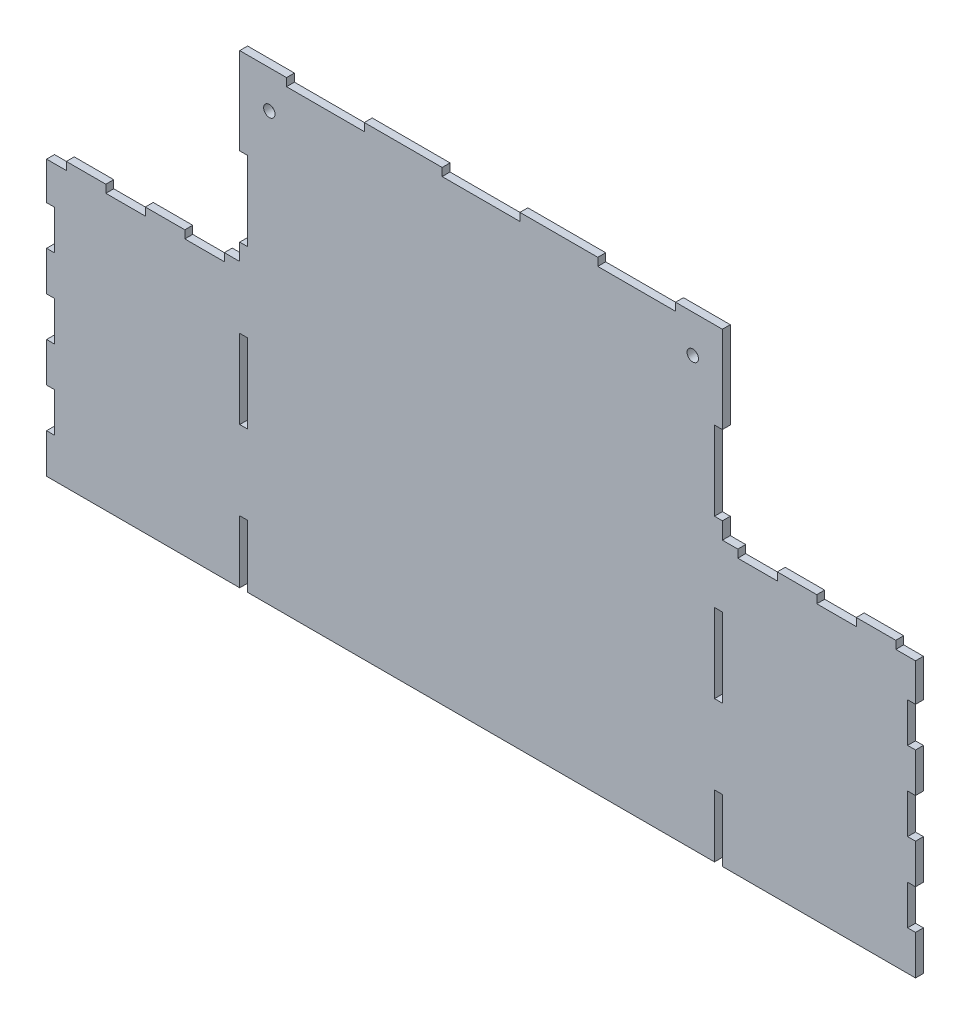
SolidWorks part; units mm, degrees
ref_plane "Front Plane" through (0, 0, 0) normal (0, 0, 1) x (1, 0, 0)
ref_plane "Top Plane" through (0, 0, 0) normal (0, 1, 0) x (1, 0, 0)
ref_plane "Right Plane" through (0, 0, 0) normal (1, 0, 0) x (0, 0, -1)
sketch "Sketch1" plane through (0, 0, 0) normal (0, 0, 1) x (1, 0, 0)
  line L1 (-77.597, 74.803) -> (77.597, 74.803)
  line L2 (-77.597, 74.803) -> (-77.597, -74.803)
  line L3 (-77.597, -74.803) -> (77.597, -74.803)
  line L4 (77.597, 74.803) -> (77.597, -74.803)
  line L5 (-77.597, 74.803) -> (77.597, -74.803) construction
  line L6 (-77.597, -74.803) -> (77.597, 74.803) construction
  point P0 (0, 0)
  dimension "D1" = 155.194
  dimension "D2" = 149.606
extrude "Boss-Extrude1" add sketch "Sketch1" along normal blind 2.54
sketch "Sketch2" plane through (0, 0, 2.54) normal (0, 0, 1) x (1, 0, 0)
  line L1 (-77.597, -74.803) -> (-139.7, -74.803)
  line L2 (-77.597, -74.803) -> (-77.597, 16.0655)
  line L3 (-77.597, 16.0655) -> (-139.7, 16.0655)
  line L4 (-139.7, -74.803) -> (-139.7, 16.0655)
  dimension "D1" = 62.103
  dimension "D2" = 90.8685
extrude "Boss-Extrude2" add sketch "Sketch2" against normal blind 2.54
sketch "Sketch3" plane through (0, 0, 2.54) normal (0, 0, 1) x (1, 0, 0)
  line L0 (-77.597, 74.803) -> (-77.597, 16.0655) construction
  line L1 (-77.597, 46.863) -> (-75.057, 46.863)
  line L2 (-77.597, 46.863) -> (-77.597, 21.463)
  line L3 (-77.597, 21.463) -> (-75.057, 21.463)
  line L4 (-75.057, 46.863) -> (-75.057, 21.463)
  line L5 (77.597, 74.803) -> (-77.597, 74.803) construction
  dimension "D1" = 27.94
  dimension "D2" = 25.4
  dimension "D3" = 2.54
extrude "Cut-Extrude1" cut sketch "Sketch3" against normal through all
pattern_linear "LPattern1" count 3 spacing 50.8 along (0, -1, 0) of "Cut-Extrude1"
mirror "Mirror1" about plane through (0, 0, 0) normal (1, 0, 0) of "LPattern1", "Boss-Extrude2", "Cut-Extrude1"
sketch "Sketch4" plane through (0, 0, 2.54) normal (0, 0, 1) x (1, 0, 0)
  line L0 (-77.597, 16.0655) -> (-139.7, 16.0655) construction
  line L1 (-146.05, 16.0655) -> (-133.35, 16.0655)
  line L2 (-146.05, 16.0655) -> (-146.05, 13.5255)
  line L3 (-146.05, 13.5255) -> (-133.35, 13.5255)
  line L4 (-133.35, 16.0655) -> (-133.35, 13.5255)
  line L5 (-139.7, 16.0655) -> (-139.7, -74.803) construction
  dimension "D1" = 12.7
  dimension "D2" = 2.54
  dimension "D3" = 6.35
extrude "Cut-Extrude2" cut sketch "Sketch4" against normal through all
pattern_linear "LPattern2" count 3 spacing 25.4 along (1, 0, 0) of "Cut-Extrude2"
mirror "Mirror2" about plane through (0, 0, 0) normal (1, 0, 0) of "LPattern2", "Cut-Extrude2"
sketch "Sketch5" plane through (0, 0, 2.54) normal (0, 0, 1) x (1, 0, 0)
  line L0 (-139.7, -74.803) -> (-77.597, -74.803) construction
  line L1 (-139.7, -62.103) -> (-137.16, -62.103)
  line L2 (-139.7, -62.103) -> (-139.7, -49.403)
  line L3 (-139.7, -49.403) -> (-137.16, -49.403)
  line L4 (-137.16, -62.103) -> (-137.16, -49.403)
  line L5 (-139.7, 13.5255) -> (-139.7, -74.803) construction
  point P4 (-138.43, -62.103)
  dimension "D1" = 2.54
  dimension "D2" = 12.7
  dimension "D3" = 12.7
extrude "Cut-Extrude3" cut sketch "Sketch5" against normal blind 2.54
pattern_linear "LPattern3" count 4 spacing 25.4 along (0, 1, 0) of "Cut-Extrude3"
mirror "Mirror3" about plane through (0, 0, 0) normal (1, 0, 0) of "LPattern3", "Cut-Extrude3"
sketch "Sketch6" plane through (0, 0, 2.54) normal (0, 0, 1) x (1, 0, 0)
  line L0 (77.597, 74.803) -> (-77.597, 74.803) construction
  line L1 (-62.5475, 74.803) -> (-37.5285, 74.803)
  line L2 (-62.5475, 74.803) -> (-62.5475, 72.263)
  line L3 (-62.5475, 72.263) -> (-37.5285, 72.263)
  line L4 (-37.5285, 74.803) -> (-37.5285, 72.263)
  line L5 (-77.597, 74.803) -> (-77.597, 46.863) construction
  dimension "D1" = 15.0495
  dimension "D2" = 25.019
  dimension "D3" = 2.54
extrude "Cut-Extrude4" cut sketch "Sketch6" against normal blind 2.54
pattern_linear "LPattern4" count 3 spacing 50.038 along (1, 0, 0) of "Cut-Extrude4"
hole_wizard "#6 Clearance Hole1" positions "Sketch8" profile "Sketch9" hole size "#6" standard "ANSI Inch"
sketch "Sketch8" plane through (0, 0, 2.54) normal (0, 0, 1) x (1, 0, 0)
  line L0 (-77.597, 74.803) -> (-77.597, 46.863) construction
  line L2 (77.597, 46.863) -> (77.597, 74.803) construction
  line L3 (-62.5475, 72.263) -> (-37.5285, 72.263) construction
  point P0 (-68.072, 62.738)
  point P2 (68.072, 62.738)
  dimension "D1" = 9.525
  dimension "D2" = 9.525
  dimension "D3" = 9.525
sketch "Sketch9" plane through (-68.072, 62.738, 2.54) normal (1, 0, 0) x (0, -1, 0)
  line L0 (0, 0) -> (0, 10.4969)
  line L1 (0, 10.4969) -> (1.8288, 9.398)
  line L2 (1.8288, 9.398) -> (1.8288, 0)
  line L5 (1.8288, 0) -> (0, 0)
  line L10 (0, 10.4969) -> (-1.8288, 9.398) construction
  line L11 (0, -6.35) -> (0, 107.95) construction
  dimension "Hole Dia." = 3.6576
  dimension "Hole Depth" = 9.398
  dimension "Drill Angle" = 118
